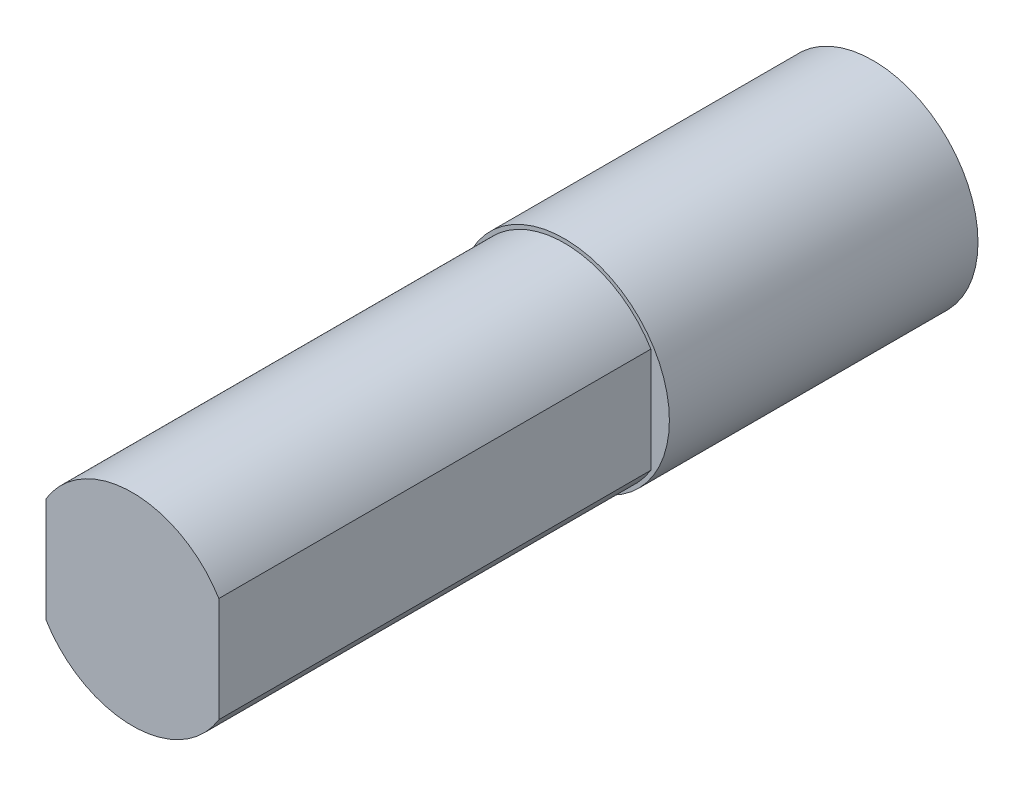
SolidWorks part; units mm, degrees
ref_plane "Front Plane" through (0, 0, 0) normal (0, 0, 1) x (1, 0, 0)
ref_plane "Top Plane" through (0, 0, 0) normal (0, 1, 0) x (1, 0, 0)
ref_plane "Right Plane" through (0, 0, 0) normal (1, 0, 0) x (0, 0, -1)
sketch "Sketch2" plane through (0, 0, 0) normal (0, 0, 1) x (1, 0, 0)
  line L0 (-1.7, -1.3162) -> (-1.7, 1.3162)
  circle A0 centre (0, 0) radius 3.4
  arc A2 (-1.7, 1.3162) -> (-1.7, -1.3162) centre (0, 0) cw
  point P4 (0, 0)
  point P7 (0, 0)
  dimension "D1" = 6.8
  dimension "D2" = 2.15
  dimension "D3" = 1.7
extrude "Boss-Extrude1" add sketch "Sketch2" along normal blind 8
sketch "Sketch3" plane through (0, 0, 8) normal (0, 0, 1) x (1, 0, 0)
  circle A0 centre (0, 0) radius 3.4
  dimension "D1" = 6.8
extrude "Boss-Extrude2" add sketch "Sketch3" along normal blind 2
sketch "Sketch4" plane through (0, 0, 10) normal (0, 0, 1) x (1, 0, 0)
  line L2 (-3.4, 0) -> (3.4, 0) construction
  line L3 (-2.8, -1.7) -> (-2.8, 1.7)
  line L4 (2.8, -1.7) -> (2.8, 1.7)
  circle A4 centre (0, 0) radius 3.4 construction
  arc A6 (-2.8, 1.7) -> (2.8, 1.7) centre (0, 0) cw
  arc A7 (-2.8, -1.7) -> (2.8, -1.7) centre (0, 0) ccw
  point P5 (2.25, -1.5142)
  point P7 (-2.8, 0)
  point P10 (2.8, 0)
  point P12 (2.25, 1.5199)
  point P13 (2.25, 1.5)
  dimension "D1" = 2.8
  dimension "D2" = 2.8
  dimension "D3" = 3.4
  dimension "D4" = 3.4
extrude "Boss-Extrude3" add sketch "Sketch4" along normal blind 14
